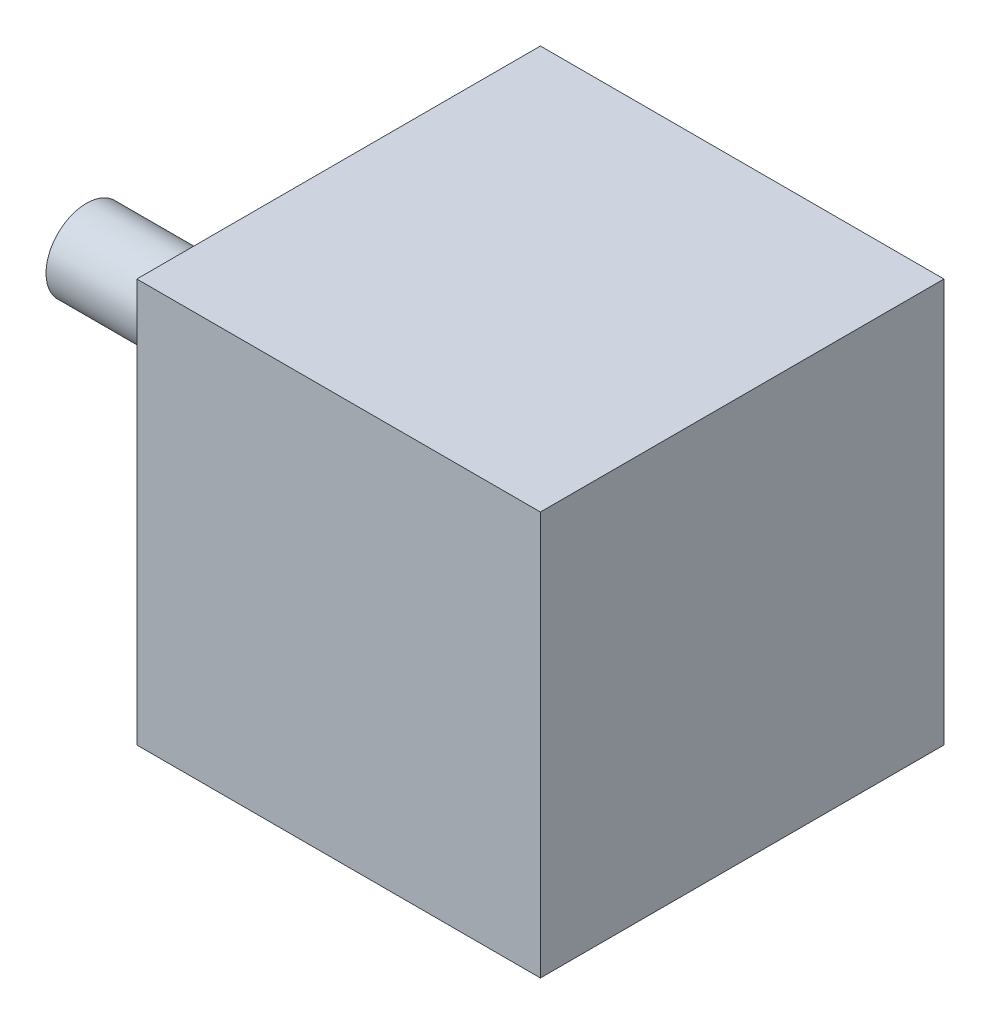
SolidWorks part; units mm, degrees
ref_plane "Front Plane" through (0, 0, 0) normal (1, 0, 0) x (0, 1, 0)
ref_plane "Top Plane" through (0, 0, 0) normal (0, 0, 1) x (0, 1, 0)
ref_plane "Right Plane" through (0, 0, 0) normal (0, 1, 0) x (-1, 0, 0)
sketch "Sketch2" plane through (0, 0, 0) normal (0, 0, 1) x (0, 1, 0)
  line L1 (-20, 20) -> (20, 20)
  line L2 (-20, 20) -> (-20, -20)
  line L3 (-20, -20) -> (20, -20)
  line L4 (20, 20) -> (20, -20)
  line L5 (-20, 20) -> (20, -20) construction
  line L6 (-20, -20) -> (20, 20) construction
  point P0 (0, 0)
  dimension "D1" = 40
extrude "Boss-Extrude1" add sketch "Sketch2" along normal blind 40
sketch "Sketch3" plane through (-20, 0, 0) normal (-1, 0, 0) x (0, -1, 0)
  line L0 (-20, 40) -> (20, 0) construction
  circle A0 centre (0, 20) radius 4
  dimension "D1" = 8
extrude "Boss-Extrude2" add sketch "Sketch3" along normal blind 25
